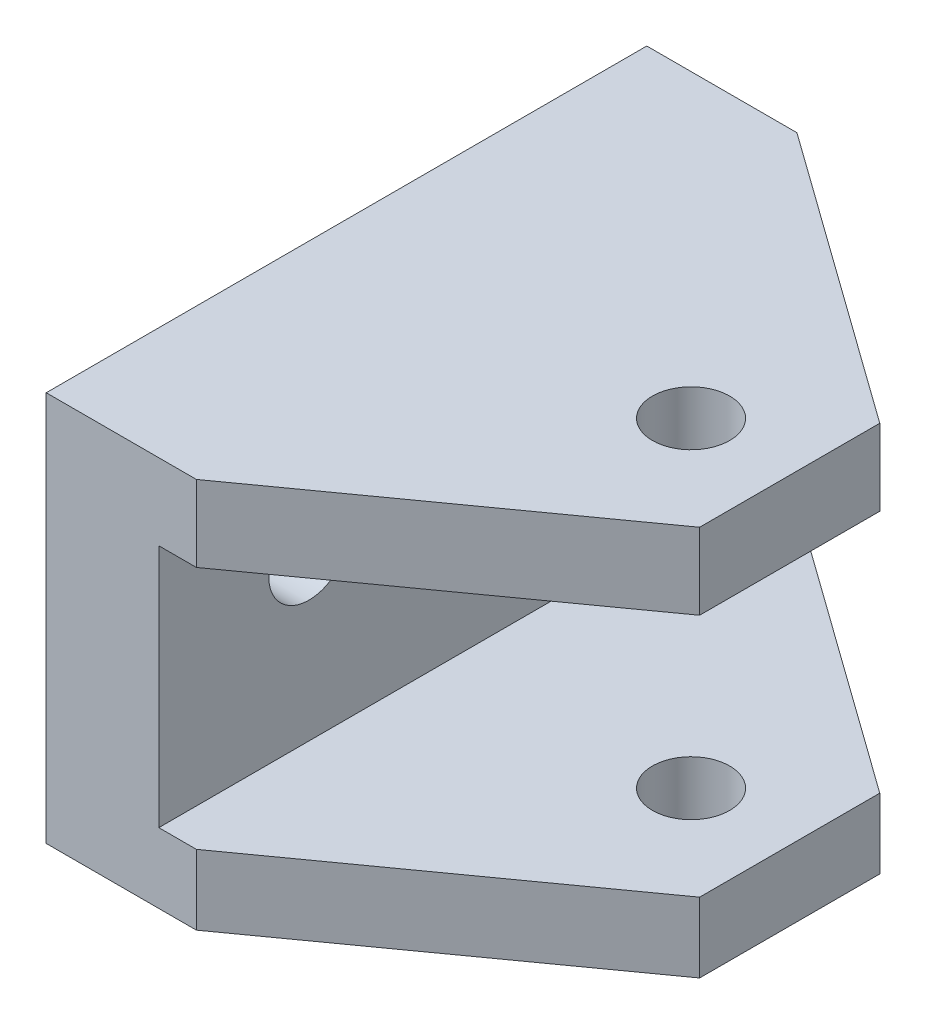
SolidWorks part; units mm, degrees
material "Custom Plastic"
ref_plane "X-Y Datum" through (0, 0, 0) normal (0, 0, 1) x (1, 0, 0)
ref_plane "X-Z Datum" through (0, 0, 0) normal (0, 1, 0) x (1, 0, 0)
ref_plane "Y-Z Datum" through (0, 0, 0) normal (1, 0, 0) x (0, 0, -1)
sketch "Sketch1" plane through (0, 0, 0) normal (0, 0, 1) x (1, 0, 0)
  line L0 (0, 1.7916) -> (0, 34.8116)
  line L1 (0, 34.8116) -> (41.8453, 34.8116)
  line L2 (41.8453, 34.8116) -> (41.8453, 28.3637)
  line L3 (41.8453, 28.3637) -> (9.525, 28.3637)
  line L4 (9.525, 28.3637) -> (9.525, 7.7135)
  line L5 (9.525, 7.7135) -> (41.8453, 7.7135)
  line L6 (41.8453, 7.7135) -> (41.8453, 1.7916)
  line L7 (0, 1.7916) -> (41.8453, 1.7916)
  line L8 (32.9553, 34.8116) -> (32.9553, 1.7916) construction
  line L9 (0, 21.4305) -> (9.525, 21.4305) construction
  line L10 (-200003.822, 21.4305) -> (200058.8771, 21.4305) construction
  line L11 (0, -10.6311) -> (0, 37.657) construction
  circle A0 centre (32.9553, 18.0386) radius 10.3251 construction
  dimension "D3" = 20.6502
  dimension "D1" = 20.6502
  dimension "D2" = 33.02
  dimension "D4" = 8.89
  dimension "D5" = 9.525
extrude "Boss-Extrude1" add sketch "Sketch1" along normal blind 50.8
sketch "Sketch2" plane through (9.525, 0, 0) normal (1, 0, 0) x (0, 0, -1)
  line L0 (-25.4, 28.3637) -> (-25.4, 7.7135) construction
  line L1 (-50.8, 28.3637) -> (0, 28.3637) construction
  line L2 (-50.8, 7.7135) -> (0, 7.7135) construction
  line L3 (-38.1, 21.4305) -> (-12.7, 21.4305) construction
  line L4 (-12.7, 21.4305) -> (0, 21.4305) construction
  line L6 (0, 28.3637) -> (0, 7.7135) construction
  circle A0 centre (-38.1, 21.4305) radius 3.4
  circle A1 centre (-12.7, 21.4305) radius 3.4
  dimension "D1" = 6.8
  dimension "D2" = 25.4
  dimension "D3" = 12.7
extrude "M8x1.25 Threaded Holes" cut sketch "Sketch2" against normal blind 50.8
sketch "Sketch3" plane through (0, 34.8116, 0) normal (0, 1, 0) x (1, 0, 0)
  line L0 (0, -25.4) -> (41.8453, -25.4) construction
  line L1 (0, -50.8) -> (0, 0) construction
  line L2 (41.8453, -50.8) -> (41.8453, 0) construction
  line L3 (12.7, 0) -> (37.4892, -17.78)
  line L4 (37.4892, -17.78) -> (37.4892, -33.02)
  line L5 (37.4892, -33.02) -> (12.7, -50.8)
  line L6 (41.8453, -50.8) -> (0, -50.8) construction
  line L7 (12.7, -50.8) -> (41.8453, -50.8)
  line L8 (41.8453, -50.8) -> (41.8453, 0)
  line L9 (41.8453, 0) -> (12.7, 0)
  line L10 (41.8453, 0) -> (0, 0) construction
  circle A0 centre (29.1453, -25.4) radius 3.2639
  point P7 (41.8453, -25.4)
  dimension "D1" = 6.5278
  dimension "D5" = 5.08
  dimension "D2" = 12.7
  dimension "D3" = 15.24
  dimension "D4" = 12.7
extrude "Cut-Extrude2" cut sketch "Sketch3" against normal up to surface (33.02 mm away) up to face at (20.9226, 1.7916, 25.4)
thread "Thread1" pitch 1.25 start angle 0, offset 0, length 0, pitch 1.25, diameter 6.8
ref_plane "Plane1" through (9.525, 21.4305, 16.1) normal (0, -1, 0) x (0, 0, 1)
sketch "Thread Profile1" plane through (9.525, 21.4305, 16.1) normal (0, -1, 0) x (0, 0, 1)
  line L0 (0, 0) -> (0, 1.25) construction
  line L11 (0, 0) -> (0, 1.0937)
  line L12 (0, 1.0937) -> (-0.6766, 0.7031)
  line L13 (-0.6766, 0.7031) -> (-0.6766, 0.3906)
  line L15 (-0.6766, 0.3906) -> (0, 0)
  line L17 (-0.6766, 0.5469) -> (0, 0.5469) construction
  point P2 (0, 0)
  dimension "Pitch" = 1.25
  dimension "Profile_Angle" = 60
  dimension "Profile_Land" = 0.3125
  dimension "Profile_Height" = 0.6766
thread "Thread2" pitch 1.25 start angle 0, offset 0, length 0, pitch 1.25, diameter 6.8
ref_plane "Plane2" through (9.525, 21.4305, 41.5) normal (0, -1, 0) x (0, 0, 1)
sketch "Thread Profile2" plane through (9.525, 21.4305, 41.5) normal (0, -1, 0) x (0, 0, 1)
  line L0 (0, 0) -> (0, 1.25) construction
  line L11 (0, 0) -> (0, 1.0937)
  line L12 (0, 1.0937) -> (-0.6766, 0.7031)
  line L13 (-0.6766, 0.7031) -> (-0.6766, 0.3906)
  line L15 (-0.6766, 0.3906) -> (0, 0)
  line L17 (-0.6766, 0.5469) -> (0, 0.5469) construction
  point P2 (0, 0)
  dimension "Pitch" = 1.25
  dimension "Profile_Angle" = 60
  dimension "Profile_Land" = 0.3125
  dimension "Profile_Height" = 0.6766
